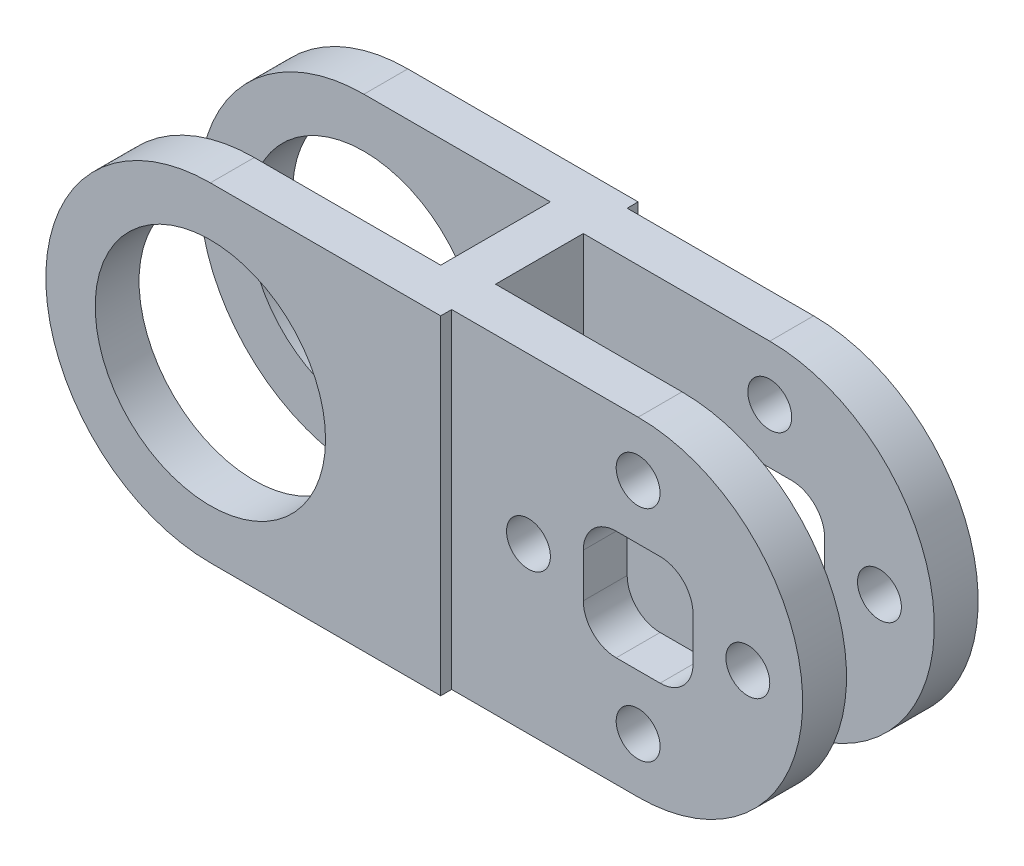
SolidWorks part; units mm, degrees
material "7075-T6，板材(SS)"
ref_plane "前视基准面" through (0, 0, 0) normal (0, 0, 1) x (1, 0, 0)
ref_plane "上视基准面" through (0, 0, 0) normal (0, 1, 0) x (1, 0, 0)
ref_plane "右视基准面" through (0, 0, 0) normal (1, 0, 0) x (0, 0, -1)
sketch "草图1" plane through (0, 0, 0) normal (0, 0, 1) x (1, 0, 0)
  line L0 (0, 0) -> (23, 0) construction
  line L1 (23, 0) -> (38, 0) construction
  line L2 (0, 15) -> (38, 15)
  line L3 (0, -15) -> (38, -15)
  arc A0 (0, 15) -> (0, -15) centre (0, 0) ccw
  arc A1 (38, -15) -> (38, 15) centre (38, 0) ccw
  dimension "D1" = 30
  dimension "D2" = 23
  dimension "D3" = 15
extrude "凸台-拉伸1" add sketch "草图1" along normal blind 18
sketch "草图2" plane through (0, 15, 0) normal (0, 1, 0) x (1, 0, 0)
  line L0 (-15, -9) -> (17, -9) construction
  line L1 (-15, 0) -> (-15, -18) construction
  line L2 (17, -9) -> (17, -3) construction
  line L4 (17, -3) -> (-15, -3)
  line L5 (17, -3) -> (17, -15)
  line L6 (17, -15) -> (-15, -15)
  line L7 (-15, -3) -> (-15, -15)
  dimension "D1" = 32
  dimension "D2" = 6
  dimension "D3" = 12
  dimension "D4" = 32
extrude "切除-拉伸1" cut sketch "草图2" against normal blind 34
sketch "草图3" plane through (0, 15, 0) normal (0, 1, 0) x (1, 0, 0)
  line L0 (53, -9) -> (21, -9) construction
  line L1 (53, -18) -> (53, 0) construction
  line L2 (21, -9) -> (21, -5) construction
  line L4 (21, -5) -> (53, -5)
  line L5 (21, -5) -> (21, -13)
  line L6 (21, -13) -> (53, -13)
  line L7 (53, -5) -> (53, -13)
  dimension "D1" = 32
  dimension "D2" = 4
  dimension "D3" = 8
  dimension "D4" = 32
extrude "切除-拉伸2" cut sketch "草图3" against normal blind 34
sketch "草图4" plane through (0, 0, 18) normal (0, 0, 1) x (1, 0, 0)
  circle A0 centre (0, 0) radius 10.5
  dimension "D1" = 21
extrude "切除-拉伸3" cut sketch "草图4" against normal blind 34
sketch "草图5" plane through (0, 0, 18) normal (0, 0, 1) x (1, 0, 0)
  line L0 (53, 0) -> (21, 0) construction
  line L1 (21, 0) -> (21, 15) construction
  line L2 (38, 15) -> (0, 15) construction
  line L4 (21, 15) -> (57.7976, 15)
  line L5 (21, 15) -> (21, -16.3402)
  line L6 (21, -16.3402) -> (57.7976, -16.3402)
  line L7 (57.7976, 15) -> (57.7976, -16.3402)
  arc A0 (38, -15) -> (38, 15) centre (38, 0) ccw construction
  dimension "D1" = 32
extrude "切除-拉伸4" cut sketch "草图5" against normal blind 2
sketch "草图6" plane through (0, 0, 0) normal (0, 0, -1) x (-1, 0, 0)
  line L0 (-53, 0) -> (-21, 0) construction
  line L1 (-21, 0) -> (-21, 15) construction
  line L3 (-21, 15) -> (-69.1941, 15)
  line L4 (-21, 15) -> (-21, -16.9478)
  line L5 (-21, -16.9478) -> (-69.1941, -16.9478)
  line L6 (-69.1941, 15) -> (-69.1941, -16.9478)
  arc A0 (-38, 15) -> (-38, -15) centre (-38, 0) ccw construction
  dimension "D1" = 32
extrude "切除-拉伸5" cut sketch "草图6" against normal blind 2
sketch "草图7" plane through (0, 0, 2) normal (0, 0, -1) x (-1, 0, 0)
  circle A0 centre (-38, 0) radius 10 construction
  circle A1 centre (-48, 0) radius 2
  circle A2 centre (-38, 10) radius 2
  circle A3 centre (-28, 0) radius 2
  circle A4 centre (-38, -10) radius 2
  point P14 (-38, 0)
  dimension "D1" = 20
  dimension "D2" = 4
  dimension "D3" = 4
extrude "切除-拉伸6" cut sketch "草图7" against normal blind 20
sketch "草图8" plane through (0, 0, 2) normal (0, 0, -1) x (-1, 0, 0)
  line L0 (-38, 5) -> (-38, -5)
  line L1 (-38, -5) -> (-33, -5)
  line L3 (-38, 5) -> (-33, 5)
  line L4 (-33, -5) -> (-33, 5)
  line L5 (-38, 0) -> (-33, 5) construction
  line L6 (-38, 0) -> (-33, -5) construction
  point P0 (-38, 0)
extrude "切除-拉伸7" cut sketch "草图8" against normal blind 20
sketch "草图9" plane through (0, 0, 0) normal (0, 0, -1) x (-1, 0, 0)
  line L3 (0, 15) -> (-21, 15)
  line L4 (-21, 15) -> (-21, -15)
  line L5 (-21, -15) -> (0, -15)
  line L6 (0, 15) -> (-21, 15)
  line L7 (-21, 15) -> (-21, -15)
  line L8 (-21, -15) -> (0, -15)
  circle A0 centre (0, 0) radius 10.5 construction
  arc A1 (0, -15) -> (0, 15) centre (0, 0) ccw
  arc A2 (0, -15) -> (0, 15) centre (0, 0) ccw
  circle A3 centre (0, 0) radius 10.5
  dimension "D1" = 0
extrude "凸台-拉伸2" add sketch "草图9" against normal blind 4
sketch "草图10" plane through (0, 0, 18) normal (0, 0, 1) x (1, 0, 0)
  line L3 (21, -15) -> (21, 15)
  line L4 (21, 15) -> (0, 15)
  line L5 (0, -15) -> (21, -15)
  line L6 (21, -15) -> (21, 15)
  line L7 (21, 15) -> (0, 15)
  line L8 (0, -15) -> (21, -15)
  circle A0 centre (0, 0) radius 10.5 construction
  arc A1 (0, 15) -> (0, -15) centre (0, 0) ccw
  arc A2 (0, 15) -> (0, -15) centre (0, 0) ccw
  circle A3 centre (0, 0) radius 10.5
  dimension "D1" = 0
extrude "凸台-拉伸3" add sketch "草图10" against normal blind 4 contours A3
sketch "草图11" plane through (0, 0, 16) normal (0, 0, 1) x (1, 0, 0)
  line L0 (33, -5) -> (38, -5) construction
  line L1 (33, 5) -> (33, -5) construction
  line L2 (38, 5) -> (33, 5) construction
  line L3 (38, 15) -> (21, 15)
  line L4 (21, 15) -> (21, -15)
  line L5 (21, -15) -> (38, -15)
  line L8 (21, -15) -> (38, -15)
  line L9 (38, -5) -> (38, 5) construction
  line L10 (21, 15) -> (21, -15) construction
  line L11 (33, -5) -> (38, -5)
  line L12 (33, 5) -> (33, -5)
  line L13 (38, 5) -> (33, 5)
  line L14 (38, -5) -> (38, 5)
  line L15 (21, 15) -> (21, -15)
  circle A0 centre (48, 0) radius 2 construction
  arc A1 (38, -15) -> (38, 15) centre (38, 0) ccw
  arc A2 (38, -15) -> (38, 15) centre (38, 0) ccw
  circle A3 centre (38, -10) radius 2 construction
  circle A5 centre (28, 0) radius 2 construction
  circle A6 centre (38, 10) radius 2 construction
  circle A7 centre (48, 0) radius 2
  circle A8 centre (38, -10) radius 2
  circle A10 centre (28, 0) radius 2
  circle A11 centre (38, 10) radius 2
  circle M6 centre (48, 0) radius 2
  circle M7 centre (38, 10) radius 2
  circle M8 centre (28, 0) radius 2
  circle M9 centre (38, -10) radius 2
  arc M10 (38, -15) -> (38, 15) centre (38, 0) ccw
  line M11 (38, 15) -> (21, 15)
  line M12 (21, 15) -> (21, -15)
  line M13 (21, -15) -> (38, -15)
  line M19 (33, -5) -> (33, 5)
  line M20 (33, 5) -> (38, 5)
  line M21 (38, 5) -> (38, -5)
  line M22 (38, -5) -> (33, -5)
  dimension "D1" = 0
extrude "凸台-拉伸4" add sketch "草图11" along normal blind 1 contours M13 M10 M11 M12 M7 M9 M8 M6 M22 M19 M20 M21
sketch "草图12" plane through (0, 0, 2) normal (0, 0, -1) x (-1, 0, 0)
  line L0 (-33, 5) -> (-38, 5) construction
  line L1 (-33, -5) -> (-33, 5) construction
  line L2 (-38, -5) -> (-33, -5) construction
  line L3 (-21, -15) -> (-21, 15)
  line L4 (-21, 15) -> (-38, 15)
  line L5 (-38, -15) -> (-21, -15)
  line L6 (-21, -15) -> (-21, 15)
  line L7 (-21, 15) -> (-38, 15)
  line L8 (-38, -15) -> (-21, -15)
  line L9 (-38, 5) -> (-38, -5) construction
  line L10 (-33, 5) -> (-38, 5)
  line L11 (-33, -5) -> (-33, 5)
  line L12 (-38, -5) -> (-33, -5)
  line L13 (-38, 5) -> (-38, -5)
  circle A0 centre (-48, 0) radius 2 construction
  arc A1 (-38, 15) -> (-38, -15) centre (-38, 0) ccw
  arc A2 (-38, 15) -> (-38, -15) centre (-38, 0) ccw
  circle A3 centre (-38, -10) radius 2 construction
  circle A5 centre (-28, 0) radius 2 construction
  circle A6 centre (-38, 10) radius 2 construction
  circle A7 centre (-48, 0) radius 2
  circle A8 centre (-38, -10) radius 2
  circle A10 centre (-28, 0) radius 2
  circle A11 centre (-38, 10) radius 2
  dimension "D1" = 0
extrude "凸台-拉伸5" add sketch "草图12" along normal blind 1
sketch "草图13" plane through (0, 0, 17) normal (0, 0, 1) x (1, 0, 0)
  line L1 (38, 5) -> (43, 5)
  line L2 (38, 5) -> (38, -5)
  line L3 (38, -5) -> (43, -5)
  line L4 (43, 5) -> (43, -5)
  dimension "D1" = 10
  dimension "D2" = 5
extrude "切除-拉伸8" cut sketch "草图13" against normal blind 19
fillet "圆角1" radius 3 6 edges at (43, -5, 3) (43, 5, 3) (33, 5, 3) (33, -5, 3) (43, -5, 15) (43, 5, 15)
